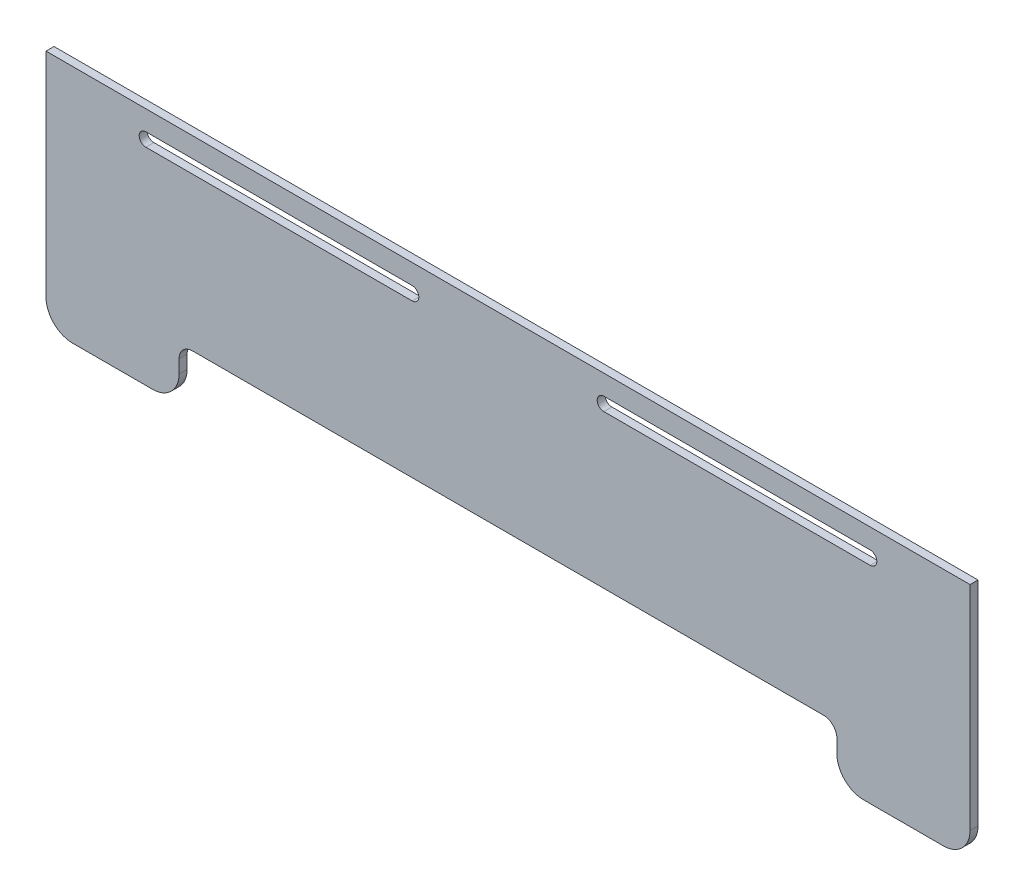
SolidWorks part; units mm, degrees
ref_plane "Front Plane" through (0, 0, 0) normal (0, 0, 1) x (1, 0, 0)
ref_plane "Top Plane" through (0, 0, 0) normal (0, 1, 0) x (1, 0, 0)
ref_plane "Right Plane" through (0, 0, 0) normal (1, 0, 0) x (0, 0, -1)
sketch "Sketch1" plane through (0, 0, 0) normal (0, 0, 1) x (1, 0, 0)
  line L0 (0, -1819.1464) -> (0, 89138.1736) construction
  line L1 (-173.5, 0) -> (173.5, 0)
  line L2 (-173.5, 0) -> (-173.5, -80)
  line L3 (-118.5, -70) -> (118.5, -70)
  line L4 (173.5, 0) -> (173.5, -80)
  line L7 (163.5, -90) -> (133.5, -90)
  line L8 (123.5, -75) -> (123.5, -80)
  line L9 (-123.5, -75) -> (-123.5, -80)
  line L10 (-163.5, -90) -> (-133.5, -90)
  line L11 (-1121.3735, -20) -> (48878.6265, -20) construction
  line L12 (175.5, -20) -> (175.5, 0) construction
  line L13 (-821.5, -10) -> (49178.5, -10) construction
  line L14 (36, -10) -> (136, -10) construction
  line L15 (36, -7.5) -> (136, -7.5)
  line L16 (36, -12.5) -> (136, -12.5)
  line L17 (-36, -10) -> (-136, -10) construction
  line L18 (-36, -7.5) -> (-136, -7.5)
  line L19 (-36, -12.5) -> (-136, -12.5)
  arc A0 (123.5, -75) -> (118.5, -70) centre (118.5, -75) ccw
  arc A1 (-123.5, -75) -> (-118.5, -70) centre (-118.5, -75) cw
  arc A2 (173.5, -80) -> (163.5, -90) centre (163.5, -80) cw
  arc A3 (133.5, -90) -> (123.5, -80) centre (133.5, -80) cw
  arc A4 (-133.5, -90) -> (-123.5, -80) centre (-133.5, -80) ccw
  arc A5 (-163.5, -90) -> (-173.5, -80) centre (-163.5, -80) cw
  arc A6 (36, -7.5) -> (36, -12.5) centre (36, -10) ccw
  arc A7 (136, -12.5) -> (136, -7.5) centre (136, -10) ccw
  arc A8 (-36, -7.5) -> (-36, -12.5) centre (-36, -10) cw
  arc A9 (-136, -12.5) -> (-136, -7.5) centre (-136, -10) cw
  point P8 (0, 0)
  point P15 (123.5, -70)
  point P19 (-123.5, -70)
  point P22 (173.5, -90)
  point P25 (123.5, -90)
  point P28 (-123.5, -90)
  point P31 (-173.5, -90)
  point P37 (175.5, -10)
  point P39 (86, -10)
  point P46 (-86, -10)
  dimension "D6" = 5
  dimension "D7" = 5
  dimension "D8" = 10
  dimension "D9" = 10
  dimension "D10" = 10
  dimension "D11" = 10
  dimension "D13" = 2.5
  dimension "D1" = 90
  dimension "D2" = 347
  dimension "D3" = 50
  dimension "D4" = 70
  dimension "D5" = 20
  dimension "D12" = 2
  dimension "D14" = 87.5
  dimension "D15" = 100
extrude "Boss-Extrude1" add sketch "Sketch1" along normal blind 3
